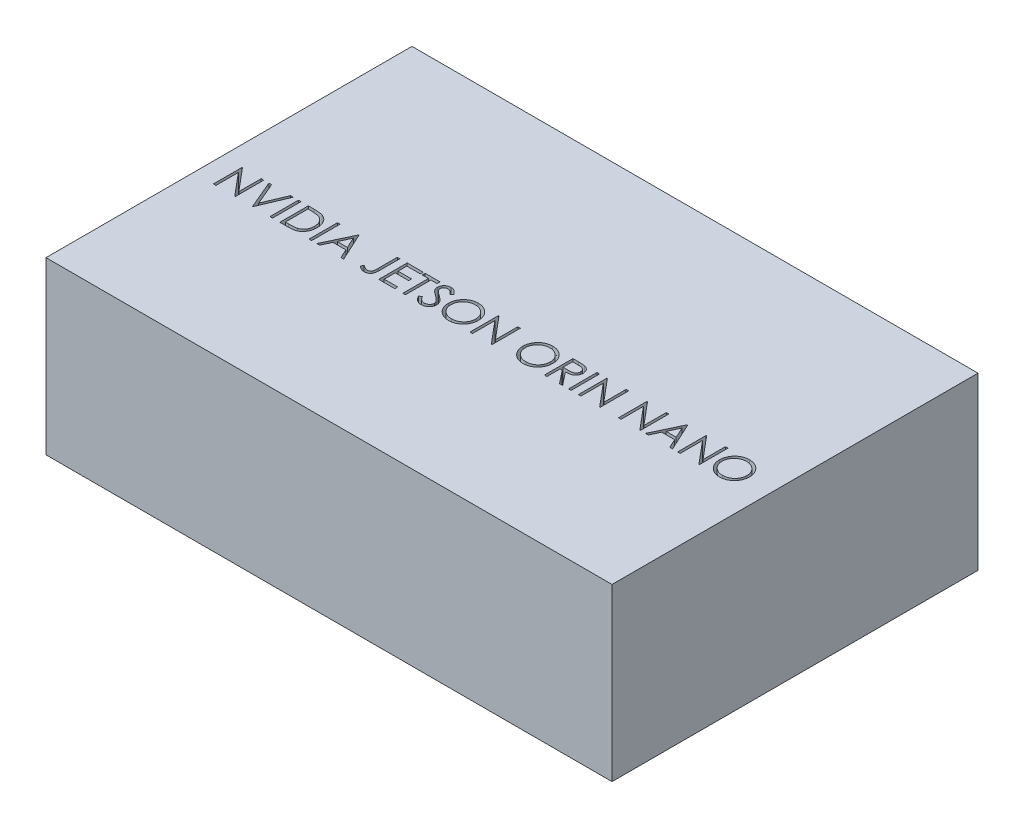
SolidWorks part; units mm, degrees
ref_plane "Front Plane" through (0, 0, 0) normal (0, 0, 1) x (1, 0, 0)
ref_plane "Top Plane" through (0, 0, 0) normal (0, 1, 0) x (1, 0, 0)
ref_plane "Right Plane" through (0, 0, 0) normal (1, 0, 0) x (0, 0, -1)
sketch "Sketch1" plane through (0, 0, 0) normal (0, 1, 0) x (1, 0, 0)
  line L1 (0, 0) -> (69.6, 0)
  line L2 (0, 0) -> (0, 45)
  line L3 (0, 45) -> (69.6, 45)
  line L4 (69.6, 0) -> (69.6, 45)
  dimension "D1" = 69.6
  dimension "D2" = 45
extrude "Boss-Extrude1" add sketch "Sketch1" along normal blind 21
sketch "Sketch2" plane through (0, 21, 0) normal (0, 1, 0) x (1, 0, 0)
  text T0 "NVIDIA JETSON ORIN NANO\r\n"
extrude "Cut-Extrude1" cut sketch "Sketch2" against normal blind 10
